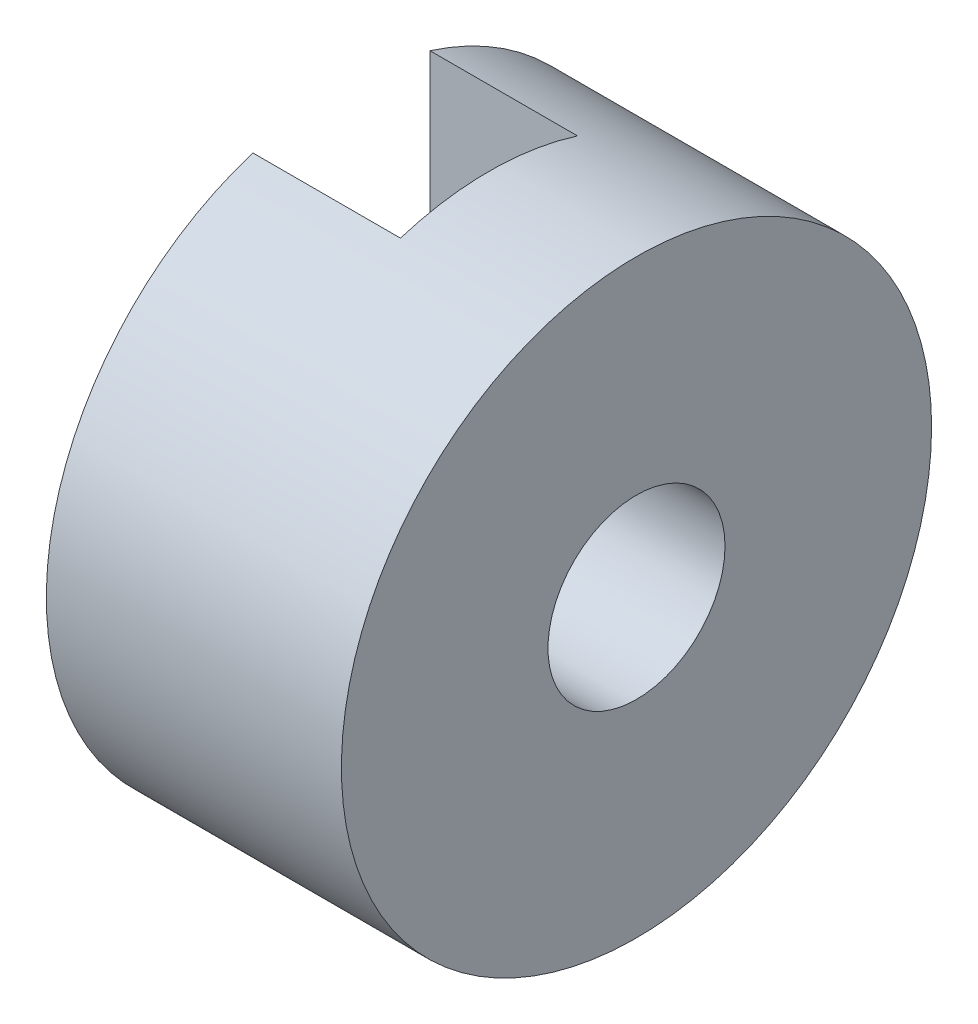
SolidWorks part; units mm, degrees
material "未指定"
ref_plane "正面" through (0, 0, 0) normal (0, 0, 1) x (1, 0, 0)
ref_plane "平面" through (0, 0, 0) normal (0, 1, 0) x (1, 0, 0)
ref_plane "右側面" through (0, 0, 0) normal (1, 0, 0) x (0, 0, -1)
sketch "ｽｹｯﾁ1" plane through (0, 0, 0) normal (1, 0, 0) x (0, 0, -1)
  circle A0 centre (0, 0) radius 3
  circle A1 centre (0, 0) radius 10
  point P5 (-0.2451, 0)
  dimension "D1" = 6
  dimension "D2" = 20
extrude "ﾎﾞｽ - 押し出し1" add sketch "ｽｹｯﾁ1" along normal blind 10
sketch "ｽｹｯﾁ2" plane through (0, 0, 0) normal (-1, 0, 0) x (0, 0, 1)
  line L0 (0, 10) -> (0, 0) construction
  line L1 (3, 10) -> (3, 0)
  line L2 (-3, 10) -> (-3, 0)
  circle A0 centre (0, 0) radius 10 construction
  arc A1 (3, 10) -> (-3, 10) centre (0, 10) ccw
  arc A2 (-3, 0) -> (3, 0) centre (0, 0) ccw
  point P5 (0, 5)
  point P10 (0, 0)
  dimension "D1" = 6
extrude "ｶｯﾄ - 押し出し1" cut sketch "ｽｹｯﾁ2" against normal blind 5
